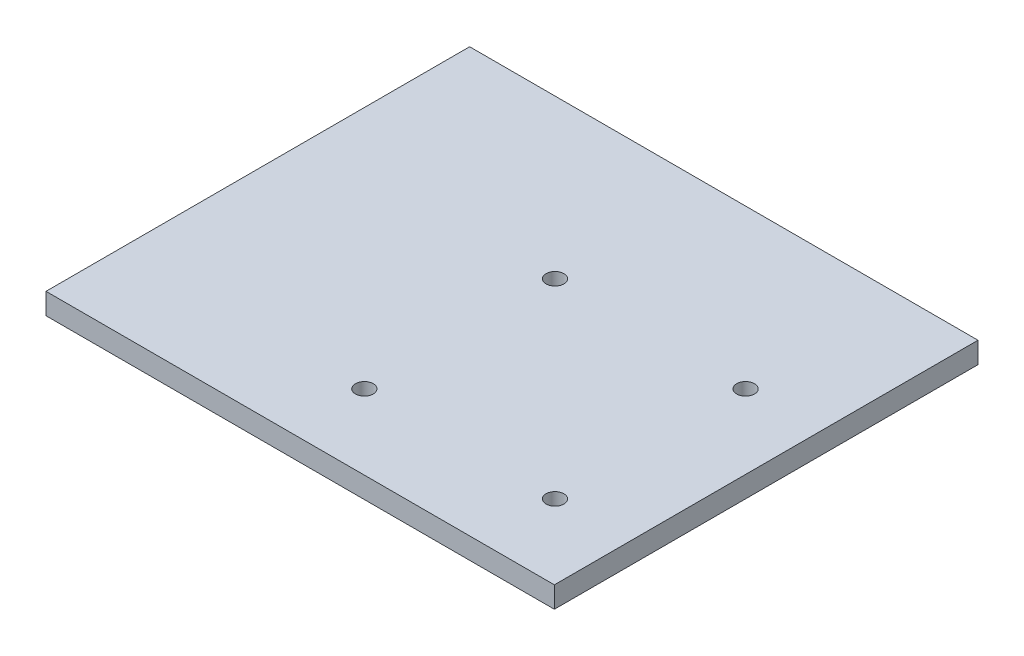
SolidWorks part; units mm, degrees
ref_plane "Front Plane" through (0, 0, 0) normal (0, 0, 1) x (1, 0, 0)
ref_plane "Top Plane" through (0, 0, 0) normal (0, 1, 0) x (1, 0, 0)
ref_plane "Right Plane" through (0, 0, 0) normal (1, 0, 0) x (0, 0, -1)
sketch "Sketch1" plane through (0, 0, 0) normal (0, 1, 0) x (1, 0, 0)
  line L0 (-152.4, 127) -> (152.4, -127) construction
  line L1 (-152.4, 127) -> (152.4, 127)
  line L2 (-152.4, 127) -> (-152.4, -127)
  line L3 (-152.4, -127) -> (152.4, -127)
  line L4 (152.4, 127) -> (152.4, -127)
  dimension "D1" = 254
  dimension "D2" = 304.8
extrude "Boss-Extrude1" add sketch "Sketch1" along normal blind 12.7
hole_wizard "1/2-13 Tapped Hole1" positions "Sketch2" profile "Sketch3" tap size "1/2-13" standard "ANSI Inch" end condition through all
sketch "Sketch2" plane through (0, 12.7, 0) normal (0, 1, 0) x (1, 0, 0)
  point P0 (-6.3252, 32.0952)
  point P3 (107.9748, 32.0952)
  point P6 (107.9748, -82.2048)
  point P9 (-6.3252, -82.2048)
sketch "Sketch3" plane through (-6.3252, 12.7, -32.0952) normal (1, 0, 0) x (0, 0, 1)
  line L0 (0, 0) -> (0, 12.7)
  line L1 (0, 12.7) -> (5.3581, 12.7)
  line L2 (5.3581, 12.7) -> (5.3581, 0)
  line L5 (5.3581, 0) -> (0, 0)
  line L11 (0, -6.35) -> (0, 107.95) construction
  dimension "Thru Tap Drill Dia." = 10.7163
  dimension "Thru Tap Drill Depth" = 12.7
cosmetic thread "Hole Thread1" parameters "D2"=12.7
cosmetic thread "Hole Thread2" parameters "D2"=12.7
cosmetic thread "Hole Thread3" parameters "D2"=12.7
cosmetic thread "Hole Thread4" parameters "D2"=12.7
